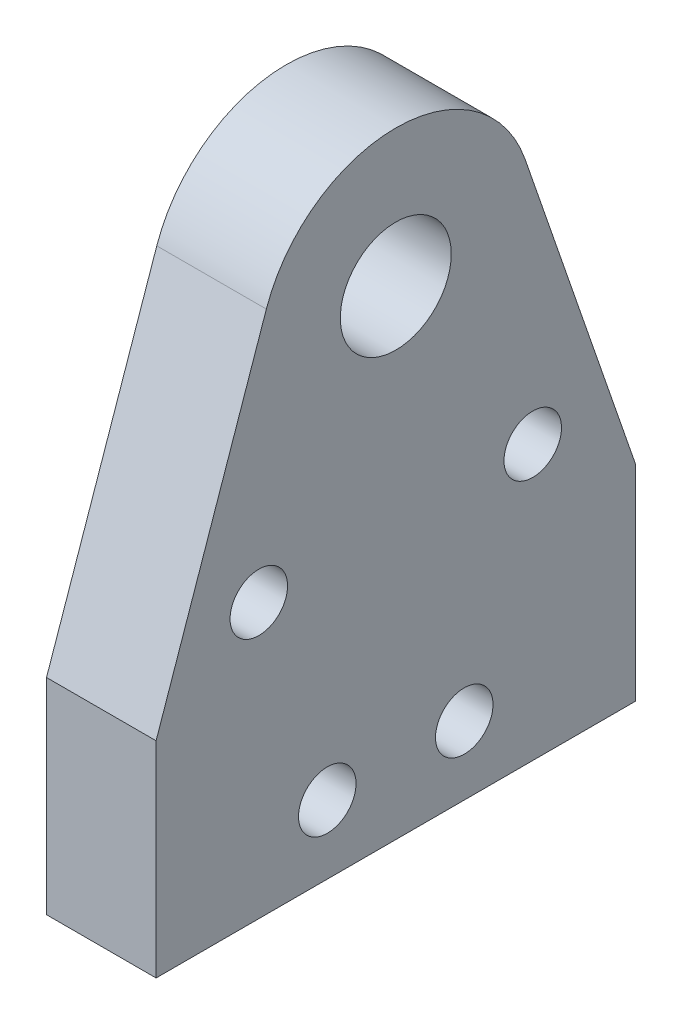
SolidWorks part; units mm, degrees
material "1060 合金"
ref_plane "前视基准面" through (0, 0, 0) normal (0, 0, 1) x (1, 0, 0)
ref_plane "上视基准面" through (0, 0, 0) normal (0, 1, 0) x (1, 0, 0)
ref_plane "右视基准面" through (0, 0, 0) normal (1, 0, 0) x (0, 0, -1)
sketch "草图1" plane through (0, 0, 0) normal (0, 1, 0) x (1, 0, 0)
  line L1 (-4, -17.5) -> (4, -17.5)
  line L2 (-4, -17.5) -> (-4, 17.5)
  line L3 (-4, 17.5) -> (4, 17.5)
  line L4 (4, -17.5) -> (4, 17.5)
  line L5 (-4, -17.5) -> (4, 17.5) construction
  line L6 (-4, 17.5) -> (4, -17.5) construction
  point P0 (0, 0)
  dimension "D1" = 35
  dimension "D2" = 8
extrude "凸台-拉伸1" add sketch "草图1" along normal blind 60
sketch "草图2" plane through (4, 0, 0) normal (1, 0, 0) x (0, 0, -1)
  line L3 (-17.5, 0) -> (-17.5, 60)
  line L4 (-17.5, 60) -> (17.5, 60)
  line L5 (17.5, 60) -> (17.5, 0)
  line L6 (-17.5, 15) -> (-8.9529, 39.7078)
  line L7 (-17.5, 18.4529) -> (-17.5, 0)
  line L8 (-17.5, 0) -> (17.5, 0) construction
  line L9 (17.5, 16.9957) -> (17.5, 0)
  line L10 (-8.9529, 39.7078) -> (-8.4567, 40.3371)
  line L11 (9.4505, 38.2692) -> (17.5, 15)
  circle A0 centre (0, 35) radius 10
  dimension "D1" = 20
  dimension "D3" = 15
  dimension "D4" = 35
  dimension "D10" = 10
  dimension "D11" = 17.5
  dimension "D2" = 0
  dimension "D5" = 0
  dimension "D6" = 0
  dimension "D7" = 0
  dimension "D8" = 15
  dimension "D9" = 10
extrude "切除-拉伸1" cut sketch "草图2" against normal blind 60
sketch "草图3" plane through (0, 0, 0) normal (0, -1, 0) x (1, 0, 0)
  line L0 (0, 12.5) -> (0, -12.5)
  circle A0 centre (0, -12.5) radius 2.1
  circle A1 centre (0, 12.5) radius 2.1
  dimension "D3" = 4.2
  dimension "D4" = 4.2
  dimension "D1" = 25
  dimension "D2" = 12.5
extrude "切除-拉伸2" cut sketch "草图3" against normal blind 10
sketch "草图4" plane through (4, 0, 0) normal (1, 0, 0) x (0, 0, -1)
  circle A0 centre (0, 35) radius 4.05
  dimension "D1" = 8.1
extrude "切除-拉伸3" cut sketch "草图4" against normal blind 46
sketch "草图5" plane through (-4, 0, 0) normal (-1, 0, 0) x (0, 0, 1)
  line L0 (-17.5, 15) -> (17.5, 15)
  line L1 (0, 15) -> (0, 5)
  line L2 (-10, 20) -> (10, 20)
  line L3 (-10, 20) -> (-10, 10)
  line L4 (-10, 10) -> (10, 10)
  line L5 (10, 20) -> (10, 10)
  line L6 (-10, 20) -> (10, 10) construction
  line L7 (-10, 10) -> (10, 20) construction
  line L8 (-5, 5) -> (5, 5)
  circle A0 centre (10, 20) radius 2.1
  circle A1 centre (-10, 20) radius 2.1
  circle A2 centre (5, 5) radius 2.1
  circle A3 centre (-5, 5) radius 2.1
  point P4 (0, 15)
  point P16 (0, 5)
  dimension "D5" = 4.2
  dimension "D6" = 4.2
  dimension "D7" = 4.2
  dimension "D8" = 4.2
  dimension "D1" = 20
  dimension "D2" = 5
  dimension "D3" = 10
  dimension "D4" = 10
extrude "切除-拉伸4" cut sketch "草图5" against normal blind 10
sketch "草图6" plane through (4, 0, 0) normal (1, 0, 0) x (0, 0, -1)
  circle A0 centre (0, 35) radius 4.05
sketch "草图7" plane through (-4, 0, 0) normal (-1, 0, 0) x (0, 0, 1)
  circle A0 centre (0, 35) radius 4.05
extrude "凸台-拉伸2" add sketch "草图7" against normal blind 2 separate body
combine bodies "组合3" operation type add bodies to combine 113 110
